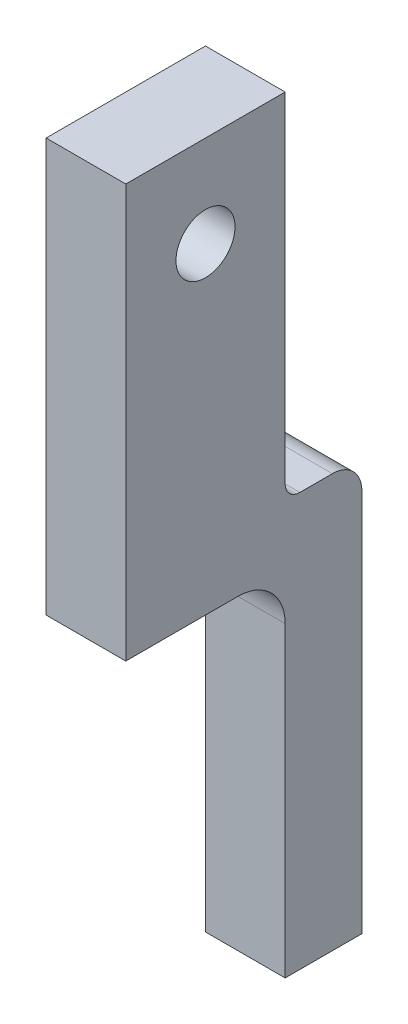
SolidWorks part; units mm, degrees
ref_plane "Front Plane" through (0, 0, 0) normal (0, 0, 1) x (1, 0, 0)
ref_plane "Top Plane" through (0, 0, 0) normal (0, 1, 0) x (1, 0, 0)
ref_plane "Right Plane" through (0, 0, 0) normal (1, 0, 0) x (0, 0, -1)
sketch "Sketch1" plane through (0, 0, 0) normal (1, 0, 0) x (0, 0, -1)
  line L1 (-465.7921, 464.0393) -> (-465.7921, 189.0393)
  line L2 (-440.7921, 164.0393) -> (-385.7921, 164.0393)
  line L3 (-335.7921, 114.0393) -> (-335.7921, -535.9607)
  line L4 (-335.7921, -535.9607) -> (-465.7921, -535.9607)
  line L5 (-465.7921, -535.9607) -> (-465.7921, -15.9607)
  line L6 (-545.7921, 64.0393) -> (-735.7921, 64.0393)
  line L7 (-735.7921, 64.0393) -> (-735.7921, 464.0393)
  line L8 (-735.7921, 464.0393) -> (-465.7921, 464.0393)
  arc A0 (-440.7921, 164.0393) -> (-465.7921, 189.0393) centre (-440.7921, 189.0393) cw
  arc A1 (-465.7921, -15.9607) -> (-545.7921, 64.0393) centre (-545.7921, -15.9607) ccw
  arc A2 (-335.7921, 114.0393) -> (-385.7921, 164.0393) centre (-385.7921, 114.0393) ccw
  dimension "D5" = 25
  dimension "D6" = 50
  dimension "D7" = 80
  dimension "D8" = 700
  dimension "D1" = 1000
  dimension "D2" = 400
  dimension "D3" = 400
  dimension "D4" = 130
extrude "Boss-Extrude1" add sketch "Sketch1" along normal blind 135
sketch "Sketch2" plane through (0, 464.0393, 0) normal (0, 1, 0) x (1, 0, 0)
  line L1 (0, -465.7921) -> (135, -465.7921)
  line L2 (0, -465.7921) -> (0, -735.7921)
  line L3 (0, -735.7921) -> (135, -735.7921)
  line L4 (135, -465.7921) -> (135, -735.7921)
extrude "Boss-Extrude2" add sketch "Sketch2" along normal blind 300
sketch "Sketch3" plane through (135, 0, 0) normal (1, 0, 0) x (0, 0, -1)
  line L0 (-465.7921, 189.0393) -> (-465.7921, 764.0393) construction
  line L1 (-735.7921, 764.0393) -> (-465.7921, 764.0393) construction
  circle A0 centre (-600.7921, 609.0393) radius 50
  dimension "D1" = 135
  dimension "D3" = 100
  dimension "D2" = 155
extrude "Cut-Extrude1" cut sketch "Sketch3" against normal through all
